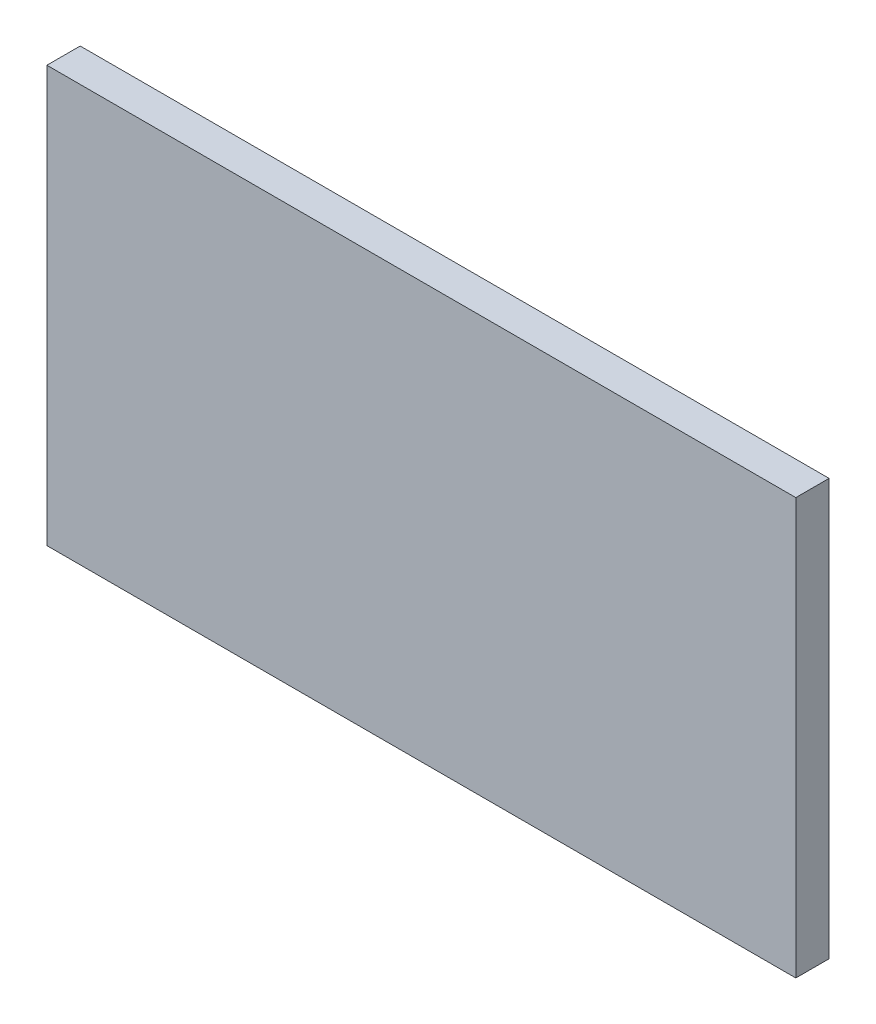
SolidWorks part; units mm, degrees
ref_plane "前视基准面" through (0, 0, 0) normal (0, 0, 1) x (1, 0, 0)
ref_plane "上视基准面" through (0, 0, 0) normal (0, 1, 0) x (1, 0, 0)
ref_plane "右视基准面" through (0, 0, 0) normal (1, 0, 0) x (0, 0, -1)
sketch "草图1" plane through (0, 0, 0) normal (0, 0, 1) x (1, 0, 0)
  line L1 (-66.4475, 33.6331) -> (113.5525, 33.6331)
  line L2 (-66.4475, 33.6331) -> (-66.4475, -66.3669)
  line L3 (-66.4475, -66.3669) -> (113.5525, -66.3669)
  line L4 (113.5525, 33.6331) -> (113.5525, -66.3669)
  dimension "D1" = 100
  dimension "D2" = 180
extrude "凸台-拉伸1" add sketch "草图1" along normal blind 8
